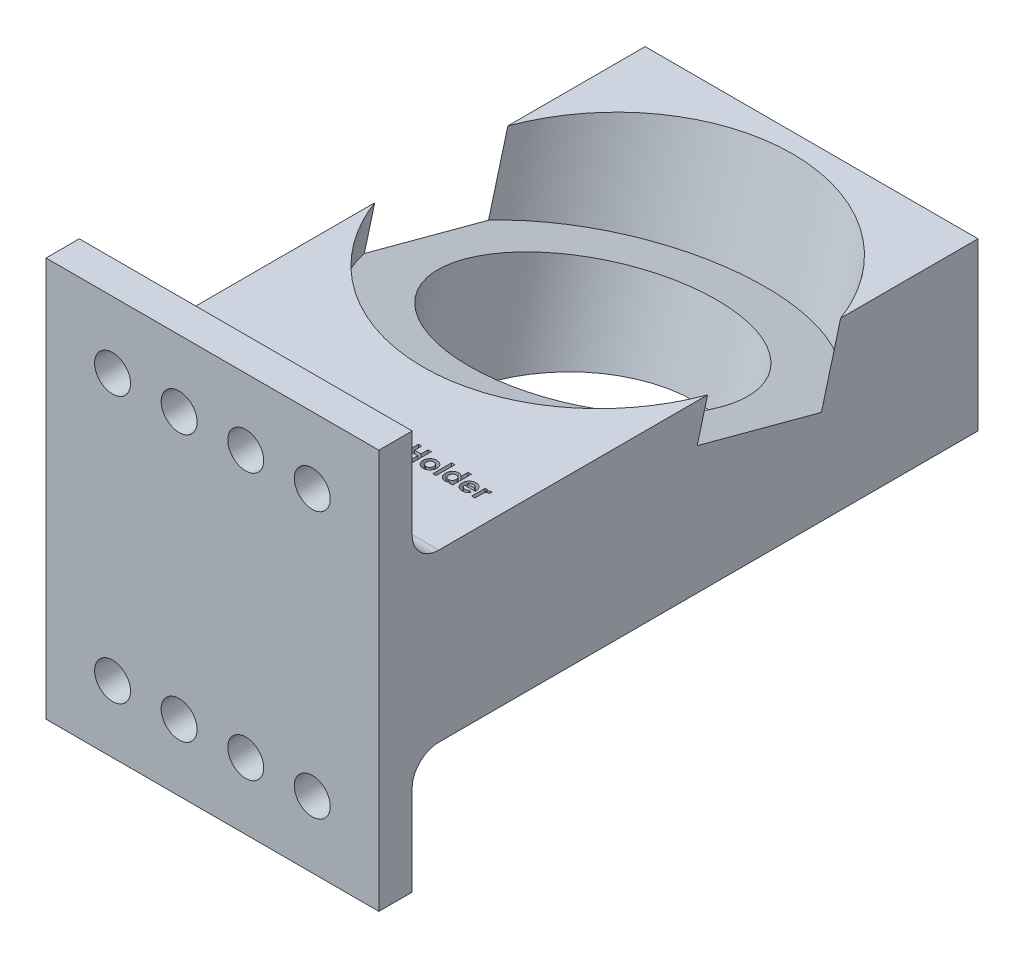
SolidWorks part; units mm, degrees
ref_plane "Front Plane" through (0, 0, 0) normal (0, 0, 1) x (1, 0, 0)
ref_plane "Top Plane" through (0, 0, 0) normal (0, 1, 0) x (1, 0, 0)
ref_plane "Right Plane" through (0, 0, 0) normal (1, 0, 0) x (0, 0, -1)
sketch "Sketch1" plane through (0, 0, 0) normal (1, 0, 0) x (0, 0, -1)
  line L1 (53.975, 15.875) -> (-53.975, 15.875)
  line L2 (53.975, 15.875) -> (53.975, -15.875)
  line L3 (53.975, -15.875) -> (-53.975, -15.875)
  line L4 (-53.975, 15.875) -> (-53.975, -15.875)
  line L5 (53.975, 15.875) -> (-53.975, -15.875) construction
  line L6 (53.975, -15.875) -> (-53.975, 15.875) construction
  point P0 (0, 0)
  dimension "D1" = 31.75
  dimension "D2" = 107.95
extrude "Boss-Extrude1" add sketch "Sketch1" along normal mid plane 63.5
sketch "Sketch2" plane through (0, 0, 0) normal (1, 0, 0) x (0, 0, -1)
  line L0 (0, -40.4243) -> (22.4049, 43.1921) construction
  line L1 (0, 0) -> (0, -41.4309) construction
  line L3 (35.8671, -1.0243) -> (26.7895, -34.9025)
  line L4 (26.7895, -34.9025) -> (3.175, -28.575)
  line L5 (3.175, -28.575) -> (21.0142, 38.0017)
  line L8 (53.975, -15.875) -> (53.975, 15.875) construction
  line L9 (-53.975, -15.875) -> (53.975, -15.875) construction
  line L10 (35.8671, -1.0243) -> (45.1289, -3.5059)
  line L11 (45.1289, -3.5059) -> (53.8904, 29.1925)
  line L12 (53.8904, 29.1925) -> (21.0142, 38.0017)
  dimension "D1" = 15
  dimension "D2" = 48.895
  dimension "D3" = 50.8
  dimension "D4" = 12.7
  dimension "D5" = 68.072
revolve "Cut-Revolve1" cut sketch "Sketch2" angle 360 about L0
sketch "Sketch3" plane through (0, 0, 53.975) normal (0, 0, 1) x (1, 0, 0)
  line L0 (31.75, 15.875) -> (31.75, -15.875) construction
  line L1 (-31.75, -38.1) -> (31.75, -38.1)
  line L2 (-31.75, -38.1) -> (-31.75, 38.1)
  line L3 (-31.75, 38.1) -> (31.75, 38.1)
  line L4 (31.75, -38.1) -> (31.75, 38.1)
  line L5 (-31.75, -38.1) -> (31.75, 38.1) construction
  line L6 (-31.75, 38.1) -> (31.75, -38.1) construction
  circle A0 centre (-19.05, 25.4) radius 3.429
  circle A1 centre (-6.35, 25.4) radius 3.429
  circle A2 centre (6.35, 25.4) radius 3.429
  circle A3 centre (19.05, 25.4) radius 3.429
  circle A4 centre (-6.35, -25.4) radius 3.429
  circle A5 centre (6.35, -25.4) radius 3.429
  circle A6 centre (19.05, -25.4) radius 3.429
  circle A7 centre (-19.05, -25.4) radius 3.429
  point P0 (0, 0)
  dimension "D2" = 6.858
  dimension "D1" = 76.2
  dimension "D3" = 12.7
  dimension "D4" = 12.7
  dimension "D5" = 4
  dimension "D6" = 2
extrude "Boss-Extrude2" add sketch "Sketch3" along normal blind 6.35
fillet "Fillet1" radius 5.08 2 edges at (0, 15.875, 53.975) (0, -15.875, 53.975)
sketch "Sketch4" plane through (0, 15.875, 0) normal (0, 1, 0) x (1, 0, 0)
  line L0 (-31.75, -36.8345) -> (31.75, -36.8345) construction
  line L1 (-31.75, 2.3895) -> (-31.75, -48.895) construction
  line L2 (31.75, 2.3895) -> (31.75, -48.895) construction
  text T0 "<b>670 kHz Caltech Holder</b>"
extrude "Cut-Extrude1" cut sketch "Sketch4" against normal blind 2.54
